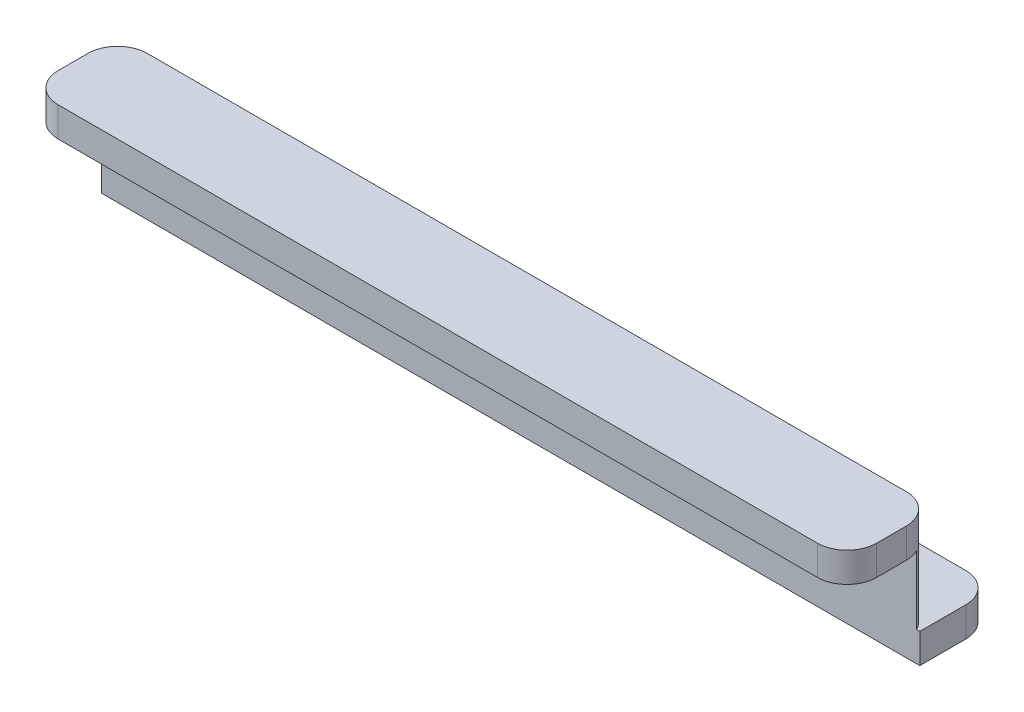
SolidWorks part; units mm, degrees
ref_plane "Front Plane" through (0, 0, 0) normal (0, 0, 1) x (1, 0, 0)
ref_plane "Top Plane" through (0, 0, 0) normal (0, 1, 0) x (1, 0, 0)
ref_plane "Right Plane" through (0, 0, 0) normal (1, 0, 0) x (0, 0, -1)
sketch "Sketch1" plane through (0, 0, 0) normal (0, 1, 0) x (1, 0, 0)
  line L1 (2, 0) -> (53.15, 0)
  line L2 (0, 2) -> (0, 4)
  line L3 (2, 6) -> (53.15, 6)
  line L4 (55.15, 2) -> (55.15, 4)
  arc A0 (53.15, 6) -> (55.15, 4) centre (53.15, 4) cw
  arc A1 (53.15, 0) -> (55.15, 2) centre (53.15, 2) ccw
  arc A2 (2, 0) -> (0, 2) centre (2, 2) cw
  arc A3 (0, 4) -> (2, 6) centre (2, 4) cw
  point P11 (0, 0)
  dimension "D1" = 2
  dimension "D2" = 2
  dimension "D3" = 55.15
  dimension "D4" = 6
extrude "Boss-Extrude1" add sketch "Sketch1" along normal blind 2
sketch "Sketch2" plane through (0, 2, 0) normal (0, 1, 0) x (1, 0, 0)
  line L4 (0, 4) -> (0, 2) construction
  line L5 (53.15, 6) -> (2, 6) construction
  line L6 (55.15, 2) -> (55.15, 4) construction
  line L7 (1.6, -21.5) -> (1.6, 2.5)
  line L8 (4, 4.9) -> (51.15, 4.9)
  line L9 (53.55, 2.5) -> (53.55, -21.5)
  line L10 (1.6, 0.0404) -> (1.6, 2.5)
  line L11 (4, 4.9) -> (51.15, 4.9)
  line L12 (53.55, 2.5) -> (53.55, 0.0404)
  line L13 (0, 4) -> (0, 2)
  line L14 (53.15, 6) -> (2, 6)
  line L15 (55.15, 2) -> (55.15, 4)
  arc A3 (2, 6) -> (0, 4) centre (2, 4) ccw construction
  arc A4 (0, 2) -> (2, 0) centre (2, 2) ccw construction
  arc A5 (4, 4.9) -> (1.6, 2.5) centre (4, 2.5) ccw
  arc A6 (53.55, 2.5) -> (51.15, 4.9) centre (51.15, 2.5) ccw
  arc A7 (4, 4.9) -> (1.6, 2.5) centre (4, 2.5) ccw
  arc A8 (53.55, 2.5) -> (51.15, 4.9) centre (51.15, 2.5) ccw
  arc A9 (55.15, 4) -> (53.15, 6) centre (53.15, 4) ccw construction
  arc A10 (53.15, 0) -> (55.15, 2) centre (53.15, 2) ccw construction
  arc A11 (2, 6) -> (0, 4) centre (2, 4) ccw
  arc A12 (0, 2) -> (1.6, 0.0404) centre (2, 2) ccw
  arc A13 (55.15, 4) -> (53.15, 6) centre (53.15, 4) ccw
  arc A14 (53.55, 0.0404) -> (55.15, 2) centre (53.15, 2) ccw
  dimension "D1" = 0.4
extrude "Boss-Extrude2" add sketch "Sketch2" against normal up to surface (8.6 mm away)
sketch "Sketch4" plane through (0, -6.6, 0) normal (0, -1, 0) x (1, 0, 0)
  line L0 (0, -4) -> (0, -8)
  line L1 (2, -10) -> (53.15, -10)
  line L2 (55.15, -8) -> (55.15, -4)
  line L3 (2, -6) -> (53.15, -6) construction
  line L4 (2, -6) -> (53.15, -6)
  arc A0 (0, -4) -> (2, -6) centre (2, -4) ccw construction
  arc A1 (53.15, -6) -> (55.15, -4) centre (53.15, -4) ccw construction
  arc A2 (0, -4) -> (2, -6) centre (2, -4) ccw
  arc A3 (53.15, -6) -> (55.15, -4) centre (53.15, -4) ccw
  arc A4 (53.15, -10) -> (55.15, -8) centre (53.15, -8) ccw
  arc A5 (0, -8) -> (2, -10) centre (2, -8) ccw
  dimension "D1" = 2
  dimension "D2" = 4
extrude "Boss-Extrude3" add sketch "Sketch4" against normal blind 2
sketch "Sketch5" [suppressed] plane through (0, 2, 0) normal (0, 1, 0) x (1, 0, 0)
  line L0 (55.15, 4) -> (55.15, 12.97)
  line L1 (53.15, 14.97) -> (2, 14.97)
  line L2 (0, 12.97) -> (0, 4)
  line L3 (0, 4) -> (2.5927, 6)
  line L4 (2.5927, 6) -> (52.7152, 6)
  line L5 (52.7152, 6) -> (55.15, 4)
  line L6 (2, 0) -> (53.15, 0) construction
  line L8 (53.15, 6) -> (2, 6) construction
  arc A0 (2, 14.97) -> (0, 12.97) centre (2, 12.97) ccw
  arc A1 (55.15, 12.97) -> (53.15, 14.97) centre (53.15, 12.97) ccw
  dimension "D1" = 2
  dimension "D2" = 14.97
extrude "Boss-Extrude4" [suppressed] add sketch "Sketch5" against normal up to surface (2 mm away)
sketch "Sketch6" [suppressed] plane through (0, 0, 0) normal (0, -1, 0) x (1, 0, 0)
  line L0 (53.55, -0.0404) -> (53.55, -2.5) construction
  line L1 (51.15, -4.9) -> (4, -4.9) construction
  line L2 (1.6, -2.5) -> (1.6, -0.0404) construction
  line L3 (53.55, -0.0404) -> (53.55, -2.5) construction
  line L4 (51.15, -4.9) -> (4, -4.9) construction
  line L5 (1.6, -2.5) -> (1.6, -0.0404) construction
  line L6 (0, -7.485) -> (55.15, -7.485) construction
  line L7 (0, -12.97) -> (0, -2) construction
  line L8 (55.15, -2) -> (55.15, -12.97) construction
  line L9 (1.6, -12.47) -> (1.6, -14.9296)
  line L10 (51.15, -10.07) -> (4, -10.07)
  line L11 (53.55, -14.9296) -> (53.55, -12.47)
  line L12 (2, -6) -> (53.15, -6) construction
  line L13 (2, -6) -> (53.15, -6)
  line L14 (0, -12.97) -> (0, -4)
  line L15 (55.15, -4) -> (55.15, -12.97)
  arc A0 (51.15, -4.9) -> (53.55, -2.5) centre (51.15, -2.5) ccw construction
  arc A1 (1.6, -2.5) -> (4, -4.9) centre (4, -2.5) ccw construction
  arc A2 (51.15, -4.9) -> (53.55, -2.5) centre (51.15, -2.5) ccw construction
  arc A3 (1.6, -2.5) -> (4, -4.9) centre (4, -2.5) ccw construction
  arc A4 (1.6, -12.47) -> (4, -10.07) centre (4, -12.47) cw
  arc A5 (51.15, -10.07) -> (53.55, -12.47) centre (51.15, -12.47) cw
  arc A6 (53.15, -6) -> (55.15, -4) centre (53.15, -4) ccw construction
  arc A7 (0, -4) -> (2, -6) centre (2, -4) ccw construction
  arc A8 (0, -12.97) -> (2, -14.97) centre (2, -12.97) ccw construction
  arc A9 (53.15, -14.97) -> (55.15, -12.97) centre (53.15, -12.97) ccw construction
  arc A10 (53.15, -6) -> (55.15, -4) centre (53.15, -4) ccw
  arc A11 (0, -4) -> (2, -6) centre (2, -4) ccw
  arc A12 (0, -12.97) -> (1.6, -14.9296) centre (2, -12.97) ccw
  arc A13 (53.55, -14.9296) -> (55.15, -12.97) centre (53.15, -12.97) ccw
extrude "Boss-Extrude5" [suppressed] add sketch "Sketch6" along normal up to surface (6.6 mm away)
sketch "Sketch7" [suppressed] plane through (0, 2, 0) normal (0, 1, 0) x (1, 0, 0)
  line L0 (2, 0) -> (53.15, 0) construction
  line L1 (20.075, 0) -> (35.075, 0)
  line L2 (20.075, 0) -> (20.075, 4.9)
  line L3 (20.075, 4.9) -> (35.075, 4.9)
  line L4 (35.075, 0) -> (35.075, 4.9)
  line L5 (27.575, -2.5935) -> (27.575, 4.9) construction
  line L7 (51.15, 4.9) -> (4, 4.9) construction
  point P9 (27.575, 0)
  point P11 (27.575, 4.9)
  dimension "D1" = 15
extrude "Cut-Extrude2" [suppressed] cut sketch "Sketch7" against normal up to next
sketch "Sketch8" plane through (0, 0, 0) normal (0, -1, 0) x (1, 0, 0)
  line L1 (55.15, 0) -> (0, 0)
  line L2 (55.15, 0) -> (55.15, -4.9)
  line L3 (55.15, -4.9) -> (0, -4.9)
  line L4 (0, 0) -> (0, -4.9)
  line L5 (2, 0) -> (53.15, 0) construction
  line L6 (55.15, -8) -> (55.15, -2) construction
  line L8 (51.15, -4.9) -> (4, -4.9) construction
  line L9 (0, -2) -> (0, -8) construction
extrude "Cut-Extrude3" cut sketch "Sketch8" along normal through all
sketch "Sketch9" [suppressed] plane through (0, 0, 0) normal (0, -1, 0) x (1, 0, 0)
  line L0 (53.15, -14.97) -> (2, -14.97) construction
  line L1 (55.15, -14.97) -> (0, -14.97)
  line L2 (55.15, -14.97) -> (55.15, -10.07)
  line L3 (55.15, -10.07) -> (0, -10.07)
  line L4 (0, -14.97) -> (0, -10.07)
  line L5 (55.15, -12.97) -> (55.15, -4.9) construction
  line L6 (0, -4.9) -> (0, -12.97) construction
  line L7 (51.15, -10.07) -> (4, -10.07) construction
extrude "Cut-Extrude4" [suppressed] cut sketch "Sketch9" along normal through all
